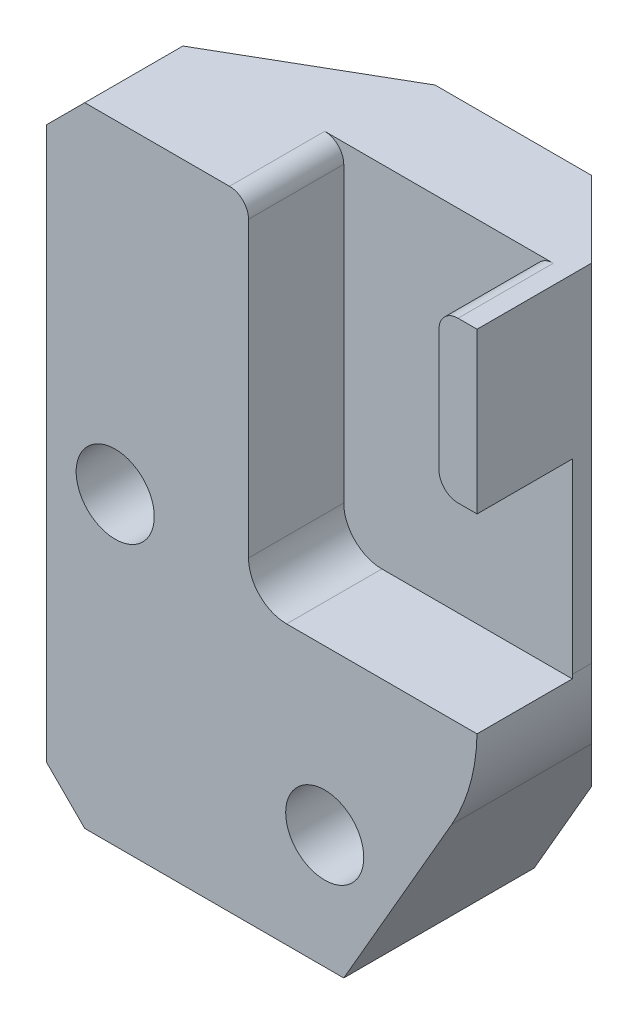
SolidWorks part; units mm, degrees
material "铸造碳钢"
ref_plane "前视基准面" through (0, 0, 0) normal (0, 0, 1) x (1, 0, 0)
ref_plane "上视基准面" through (0, 0, 0) normal (0, 1, 0) x (1, 0, 0)
ref_plane "右视基准面" through (0, 0, 0) normal (1, 0, 0) x (0, 0, -1)
sketch "草图1" plane through (0, 0, 0) normal (0, 0, 1) x (1, 0, 0)
  line L0 (0, 10) -> (0, -10) construction
  line L1 (-2.5, 10) -> (2.5, 10)
  line L2 (-2.5, 10) -> (-2.5, -10)
  line L3 (-2.5, -10) -> (2.5, -10)
  line L4 (2.5, 10) -> (2.5, -10)
  dimension "D1" = 5
  dimension "D2" = 20
extrude "拉伸1" add sketch "草图1" along normal blind 5
sketch "Sketch1" plane through (-2.5, 0, 0) normal (-1, 0, 0) x (0, 0, 1)
  line L4 (0, 10) -> (0, -10)
  line L5 (0, -10) -> (5, -10)
  line L6 (5, -10) -> (5, 10)
  line L7 (5, 10) -> (0, 10)
  line L8 (0, 10) -> (0, -10)
  line L9 (0, -10) -> (5, -10)
  line L10 (5, -10) -> (5, 10)
  line L11 (5, 10) -> (0, 10)
  dimension "D1" = 0
extrude "Extrude1" add sketch "Sketch1" along normal blind 6.8
sketch "草图2" plane through (0, 0, 0) normal (0, 0, 1) x (1, 0, 0)
  line L0 (-1.5, 7) -> (-1.5, -7)
  line L1 (-1.5, 0) -> (-7, 0)
  line L2 (0, 0) -> (-1.5, 0)
  line L3 (2.5, -10) -> (2.5, 10) construction
  line L4 (-1.5, -2) -> (-7, -2)
  dimension "D1" = 14
  dimension "D2" = 5.5
  dimension "D3" = 4
  dimension "D4" = 5.5
  dimension "D5" = 5
hole_wizard "M2.5 Tapped Hole1" positions "3D草图1" profile "草图3" tap size "M2.5" standard "GB"
sketch3d "3D草图1"
  point P3 (-1.5, -7, 0)
  point P7 (-7, -2, 0)
sketch "草图3" plane through (-1.5, -7, 0) normal (1, 0, 0) x (0, 1, 0)
  line L0 (0, 0) -> (0, 6.9659)
  line L1 (0, 6.9659) -> (1.025, 6.35)
  line L2 (1.025, 6.35) -> (1.025, 0)
  line L5 (1.025, 0) -> (0, 0)
  line L10 (0, 6.9659) -> (-1.025, 6.35) construction
  line L11 (0, -6.35) -> (0, 107.95) construction
  dimension "Tap Drill Dia." = 2.05
  dimension "Tap Drill Depth" = 6.35
  dimension "Drill Angle" = 118
cosmetic thread "Hole Thread1" parameters "D1"=5, "D2"=2.5
cosmetic thread "Hole Thread2" parameters "D1"=5, "D2"=2.5
chamfer "倒角1" [suppressed] distance 0.5 angle 45
sketch "Sketch2" plane through (0, 0, 5) normal (0, 0, -1) x (-1, 0, 0)
  line L0 (-1.5, -1.7) -> (-1.5, 5.5)
  line L1 (-0.5, 6.5) -> (2.5, 6.5)
  line L2 (3.5, 5.5) -> (3.5, -1.7)
  line L3 (2.5, -2.7) -> (-0.5, -2.7)
  line L4 (1, 0) -> (1, 6.5) construction
  line L5 (-2.5, -10) -> (-2.5, 10) construction
  line L6 (1.5, 0) -> (7, 0) construction
  arc A0 (-0.5, -2.7) -> (-1.5, -1.7) centre (-0.5, -1.7) cw
  arc A1 (3.5, -1.7) -> (2.5, -2.7) centre (2.5, -1.7) cw
  arc A2 (2.5, 6.5) -> (3.5, 5.5) centre (2.5, 5.5) cw
  arc A3 (-1.5, 5.5) -> (-0.5, 6.5) centre (-0.5, 5.5) cw
  dimension "D2" = 1
  dimension "D1" = 0
  dimension "D3" = 5
  dimension "D4" = 9.2
  dimension "D5" = 6.5
  dimension "D6" = 3.5
extrude "Extrude2" cut sketch "Sketch2" along normal blind 2.5
chamfer "Chamfer1" [suppressed] distance 1 angle 45
sketch "Sketch3" plane through (0, 0, 5) normal (0, 0, 1) x (1, 0, 0)
  line L1 (-9.3, 10) -> (2.5, 10)
  line L2 (-9.3, 10) -> (-9.3, 6.5)
  line L3 (-9.3, 6.5) -> (2.5, 6.5)
  line L4 (2.5, 10) -> (2.5, 6.5)
  dimension "D1" = 3.5
  dimension "D2" = 11.8
extrude "Extrude3" cut sketch "Sketch3" against normal up to surface (5 mm away) up to face at (-2.525, -7, 0)
sketch "Sketch4" plane through (0, 0, 5) normal (0, 0, -1) x (-1, 0, 0)
  line L0 (-1.5, 8) -> (-1.5, 3)
  line L1 (-1.5, -1.7) -> (-1.5, 5.5) construction
  line L2 (-1.5, 3) -> (3.5, 3)
  line L3 (3.5, 3) -> (3.5, 8)
  line L4 (3.5, 5.5) -> (3.5, -1.7) construction
  line L5 (3.5, 8) -> (-1.5, 8)
  line L7 (-2.5, 6.5) -> (9.3, 6.5) construction
  dimension "D1" = 1.5
  dimension "D2" = 5
extrude "Extrude4" cut sketch "Sketch4" against normal up to surface (2.5 mm away)
chamfer "Chamfer2" [suppressed] distance 1 angle 45
chamfer "Chamfer3" [suppressed] distance 7 angle 45
sketch "Sketch7" [suppressed] plane through (0, 0, 0) normal (0, 0, -1) x (-1, 0, 0)
  line L0 (9.3, -10) -> (9.3, 6.5) construction
  line L1 (7, -2.5) -> (9.3, -2.5)
  line L2 (7, -2.5) -> (7, 2.5)
  line L3 (7, 2.5) -> (9.3, 2.5)
  line L4 (9.3, -2.5) -> (9.3, 2.5)
  arc A0 (9.3, -0.9798) -> (9.3, 0.9798) centre (7, 0) ccw construction
  arc A1 (9.3, 0.9798) -> (9.3, -0.9798) centre (7, 0) ccw construction
  circle A2 centre (7, 0) radius 1.45 construction
  circle A3 centre (7, 0) radius 1.45 construction
extrude "Extrude5" [suppressed] cut sketch "Sketch7" against normal up to surface (2 mm away)
chamfer "Chamfer4" distance 2 angle 45 1 edges at (2.5, -1.75, 0)
sketch "Sketch8" plane through (0, 0, 5) normal (0, 0, 1) x (1, 0, 0)
  line L0 (2.5, -10) -> (2.5, 6.5) construction
  line L1 (0.5, -2.7) -> (2.5, -2.7)
  line L2 (0.5, -2.7) -> (0.5, 2.3)
  line L3 (0.5, 2.3) -> (2.5, 2.3)
  line L4 (2.5, -2.7) -> (2.5, 2.3)
  dimension "D1" = 5
extrude "Extrude6" cut sketch "Sketch8" against normal up to surface (2.5 mm away) up to face at (-1, 0.631, 2.5)
sketch "Sketch9" plane through (1.5, 0, 0) normal (-1, 0, 0) x (0, 0, 1)
  line L4 (2.5, 2.3) -> (5, 2.3)
  line L5 (5, 2.3) -> (5, 6.5)
  line L6 (5, 6.5) -> (2.5, 6.5)
  line L7 (2.5, 6.5) -> (2.5, 2.3)
  line L8 (2.5, 2.3) -> (5, 2.3)
  line L9 (5, 2.3) -> (5, 6.5)
  line L10 (5, 6.5) -> (2.5, 6.5)
  line L11 (2.5, 6.5) -> (2.5, 2.3)
  dimension "D1" = 0
extrude "Extrude7" [suppressed] add sketch "Sketch9" along normal blind 1
chamfer "Chamfer5" [suppressed] distance 1 angle 45
sketch "Sketch10" plane through (0, 0, 5) normal (0, 0, 1) x (1, 0, 0)
  line L0 (-3.5, 6.5) -> (-6.5, 6.5)
  line L1 (-9.3, 6.5) -> (-3.5, 6.5) construction
  line L2 (-6.5, 6.5) -> (-3.5, 1.5)
  line L3 (-3.5, -1.7) -> (-3.5, 6.5) construction
  line L4 (-3.5, 1.5) -> (-3.5, 6.5)
  dimension "D1" = 3
  dimension "D2" = 5
extrude "Extrude8" [suppressed] cut sketch "Sketch10" against normal up to surface (2.5 mm away)
fillet "Fillet1" radius 0.5 1 edges at (1.5, 2.3, 3.75)
fillet "Fillet2" radius 0.5 2 edges at (1.5, 6.5, 3.75) (-3.5, 6.5, 3.75)
chamfer "Chamfer6" distance 3.5 angle 60 1 edges at (2.5, -10, 3.5)
chamfer "Chamfer7" [suppressed] distance 2 angle 45
sketch "Sketch12" plane through (-9.3, 0, 0) normal (-1, 0, 0) x (0, 0, 1)
  line L4 (5, 6.5) -> (0, 6.5)
  line L5 (0, 6.5) -> (0, -10)
  line L6 (0, -10) -> (5, -10)
  line L7 (5, -10) -> (5, 6.5)
  line L8 (5, 6.5) -> (0, 6.5)
  line L9 (0, 6.5) -> (0, -10)
  line L10 (0, -10) -> (5, -10)
  line L11 (5, -10) -> (5, 6.5)
  dimension "D1" = 0
extrude "Extrude11" cut sketch "Sketch12" against normal blind 0.5
sketch "Sketch13" plane through (0, 6.5, 0) normal (0, 1, 0) x (1, 0, 0)
  line L0 (-8.8, -3) -> (-8.8, 0)
  line L2 (-8.8, 0) -> (-3.6038, 0)
  line L4 (-3.6038, 0) -> (-8.8, -3)
  line L5 (0.5, 0) -> (-8.8, 0) construction
  dimension "D1" = 3
  dimension "D2" = 60
extrude "Extrude10" cut sketch "Sketch13" against normal up to surface (16.5 mm away) up to face at (-4.9, -10, 2.5)
chamfer "Chamfer9" distance 1 angle 45 2 edges at (-8.8, -10, 4) (-8.8, 6.5, 4)
fillet "Fillet3" radius 5 1 edges at (2.5, -3.9378, 3.5)
